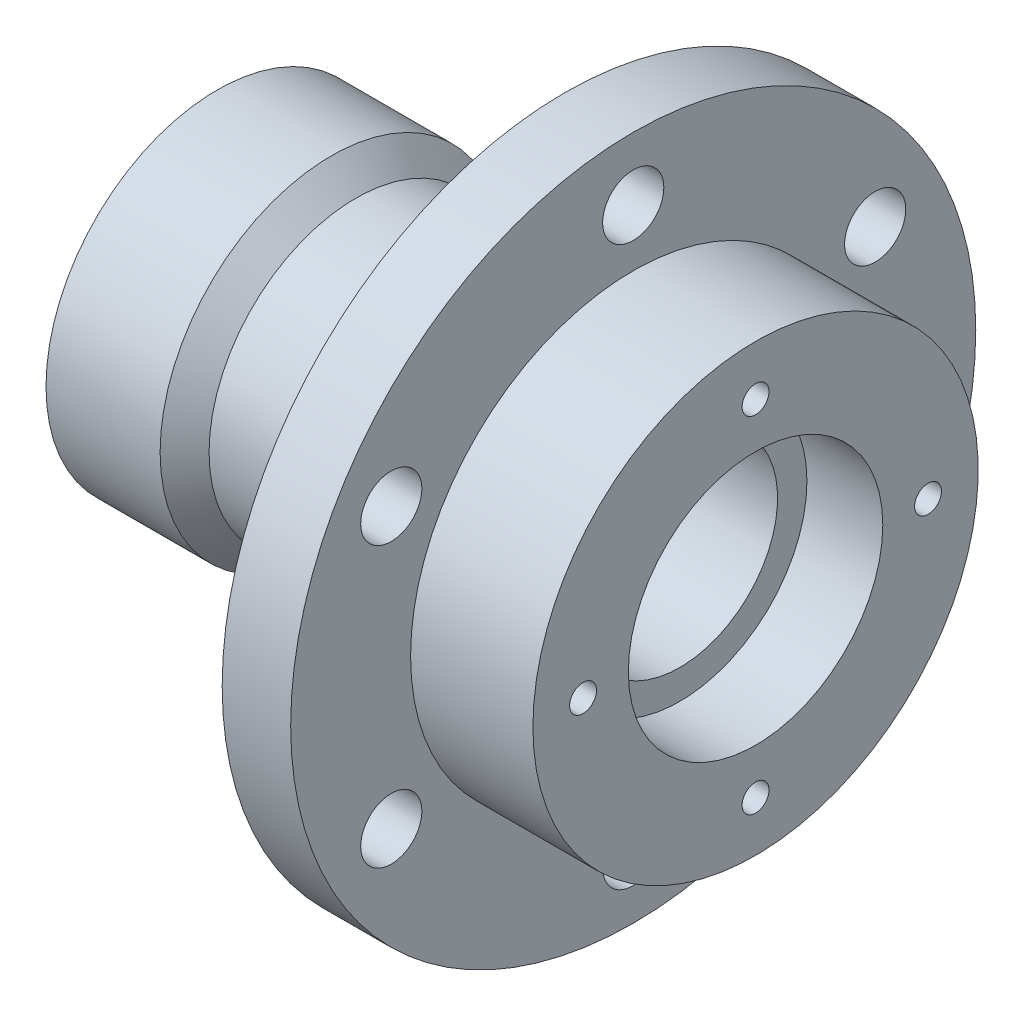
SolidWorks part; units mm, degrees
material "1.0601 (C60)"
ref_plane "Piano frontale" through (0, 0, 0) normal (0, 0, 1) x (1, 0, 0)
ref_plane "Piano superiore" through (0, 0, 0) normal (0, 1, 0) x (1, 0, 0)
ref_plane "Piano destro" through (0, 0, 0) normal (1, 0, 0) x (0, 0, -1)
sketch "Schizzo1" plane through (0, 0, 0) normal (0, 0, 1) x (1, 0, 0)
  line L0 (0, 0) -> (0, 35)
  line L1 (0, 35) -> (23.3179, 35)
  line L2 (23.3179, 35) -> (28.3179, 30)
  line L3 (28.3179, 30) -> (71, 30)
  line L4 (71, 30) -> (71, 70)
  line L5 (71, 70) -> (85, 70)
  line L6 (85, 70) -> (85, 45.5)
  line L7 (85, 45.5) -> (110, 45.5)
  line L8 (110, 45.5) -> (110, 0)
  line L9 (0, 23.5) -> (2, 23.5)
  line L10 (2, 23.5) -> (2, 24.75)
  line L11 (2, 24.75) -> (3.85, 24.75)
  line L12 (3.85, 24.75) -> (3.85, 23.5)
  line L13 (3.85, 23.5) -> (17.85, 23.5)
  line L14 (17.85, 23.5) -> (17.85, 20)
  line L15 (17.85, 20) -> (94.5, 20)
  line L16 (94.5, 20) -> (94.5, 26)
  line L17 (94.5, 26) -> (110, 26)
  line L18 (-28.7481, 0) -> (132.2673, 0) construction
  dimension "D1" = 40
  dimension "D2" = 60
  dimension "D3" = 52
  dimension "D4" = 91
  dimension "D5" = 140
  dimension "D6" = 70
  dimension "D7" = 45
  dimension "D8" = 47
  dimension "D9" = 49.5
  dimension "D10" = 47
  dimension "D11" = 2
  dimension "D12" = 1.85
  dimension "D13" = 17.85
  dimension "D14" = 15.5
  dimension "D15" = 14
  dimension "D16" = 71
  dimension "D17" = 25
revolve "Rivoluzione1" add sketch "Schizzo1" angle 360 about L18
hole_wizard "Foro Ø12.5 (12.5)-1" positions "Schizzo4" profile "Schizzo5" hole size "Ø12.5" standard "ISO"
sketch "Schizzo4" plane through (71, 0, 0) normal (-1, 0, 0) x (0, 0, 1)
  line L0 (0, 0) -> (0, 57.09) construction
  point P0 (0, 57.09)
  dimension "D1" = 57.09
sketch "Schizzo5" plane through (71, 57.09, 0) normal (0, 1, 0) x (0, 0, 1)
  line L0 (0, 0) -> (0, 17.7544)
  line L1 (0, 17.7544) -> (6.25, 13.999)
  line L2 (6.25, 13.999) -> (6.25, 0)
  line L5 (6.25, 0) -> (0, 0)
  line L10 (0, 17.7544) -> (-6.25, 13.999) construction
  line L11 (0, -6.35) -> (0, 107.95) construction
  dimension "Hole Dia." = 12.5
  dimension "Hole Depth" = 13.999
  dimension "Drill Angle" = 118
pattern_circular "RipetizioneCircolare1" count 6 over 360 about axis through (0, 0, 0) along (1, 0, 0) of "Foro Ø12.5 (12.5)-1"
hole_wizard "Foro per Vite M5-1" positions "Schizzo6" profile "Schizzo7" hole size "M5" standard "ISO"
sketch "Schizzo6" plane through (110, 0, 0) normal (1, 0, 0) x (0, 0, -1)
  line L0 (0, 0) -> (0, 35.25) construction
  point P0 (0, 35.25)
  dimension "D1" = 35.25
sketch "Schizzo7" plane through (110, 35.25, 0) normal (0, 1, 0) x (0, 0, -1)
  line L0 (0, 0) -> (0, 13.6524)
  line L1 (0, 13.6524) -> (2.75, 12)
  line L2 (2.75, 12) -> (2.75, 0)
  line L5 (2.75, 0) -> (0, 0)
  line L10 (0, 13.6524) -> (-2.75, 12) construction
  line L11 (0, -6.35) -> (0, 107.95) construction
  dimension "Hole Dia." = 5.5
  dimension "Hole Depth" = 12
  dimension "Drill Angle" = 118
pattern_circular "RipetizioneCircolare2" count 4 over 360 about axis through (0, 0, 0) along (1, 0, 0) of "Foro per Vite M5-1"
